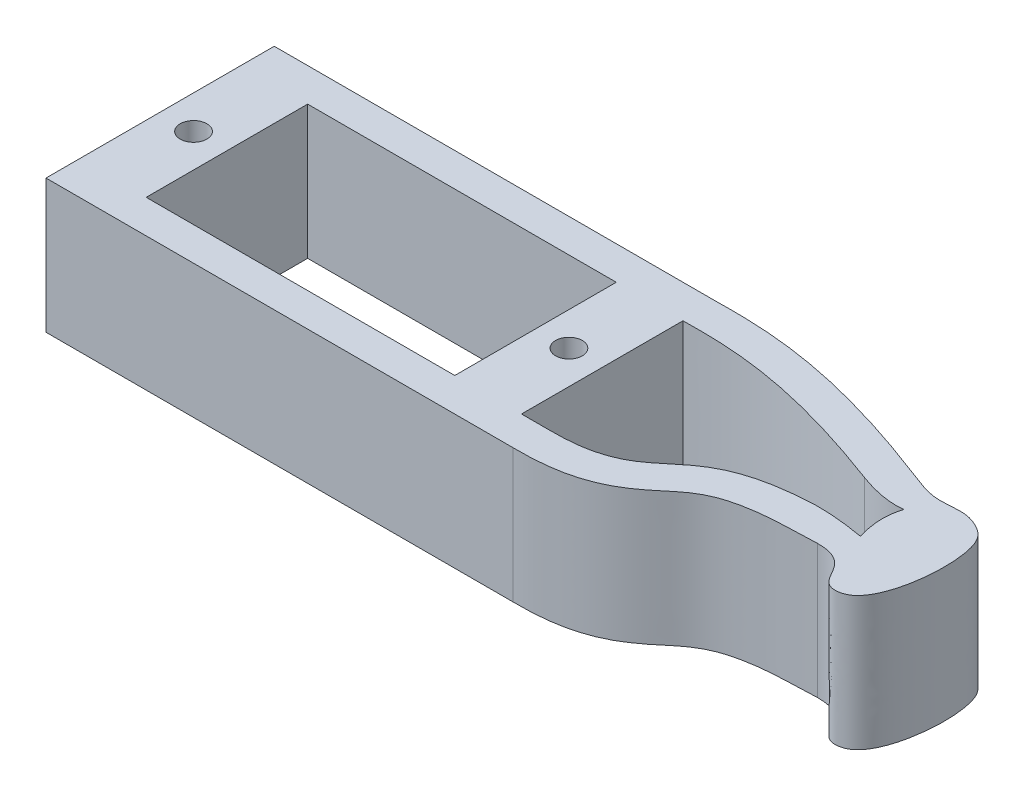
SolidWorks part; units mm, degrees
ref_plane "Спереди" through (0, 0, 0) normal (0, 0, 1) x (1, 0, 0)
ref_plane "Сверху" through (0, 0, 0) normal (0, 1, 0) x (1, 0, 0)
ref_plane "Справа" through (0, 0, 0) normal (1, 0, 0) x (0, 0, -1)
other "Configuration Table"
sketch "Эскиз1" plane through (0, 0, 0) normal (0, 1, 0) x (1, 0, 0)
  line L0 (0, 0) -> (0, -12.0852)
  line L1 (0, -12.0852) -> (23.1, -12.0852)
  line L2 (0, -12.0852) -> (28.092, -12.0852) construction
  line L3 (28.092, -12.0852) -> (28.092, 0) construction
  line L4 (0, 0) -> (23.1, 0)
  line L5 (23.1, -6.0426) -> (28.1, -6.0425) construction
  line L7 (-2.5, 2.5) -> (28.071, 2.5)
  line L9 (-2.5, -14.5852) -> (29.9653, -14.5852)
  line L11 (47.5572, -1.6341) -> (47.5572, -9.3909) construction
  line L13 (28.092, -12.0852) -> (29.9852, -12.0852)
  line L14 (0, -6.0426) -> (-5, -6.0426) construction
  line L15 (23.1, -12.0852) -> (23.1, 0)
  line L16 (0, -12.0852) -> (29.9852, -12.0852) construction
  line L17 (0, 0) -> (28.092, 0) construction
  line L18 (45.0572, -3.368) -> (45.0572, -6.9843) construction
  line L19 (-2.5, 2.5) -> (-5, 2.5)
  line L20 (-5, 2.5) -> (-5, -14.5852)
  line L21 (-5, -14.5852) -> (-2.5, -14.5852)
  line L22 (28.092, 0) -> (28.092, -12.0852)
  line L23 (-2.5, 2.5) -> (-2.5, -14.5852) construction
  circle A0 centre (-2.5, -6.0426) radius 1
  circle A1 centre (25.6, -6.0425) radius 1
  spline S0 degree 3 poles (29.9852, -12.0852) (38.2811, -12.2209) (35.1725, -7.3609) (45.0572, -6.9843) knots 0 0 0 0 1 1 1 1
  spline S1 degree 3 poles (28.092, 0) (31.819, 0.063) (36.1454, -0.0333) (45.0572, -3.368) knots 0.142072 0.142072 0.142072 0.142072 1 1 1 1
  spline S2 degree 1 poles (28.071, 2.5) (47.5572, -1.6341) knots 0 0 1 1 construction
  spline S3 degree 1 poles (29.9653, -14.5852) (47.5572, -9.3909) knots 0 0 1 1 construction
  spline S4 degree 3 poles (28.071, 2.5) (28.3289, 2.5043) (28.8356, 2.5112) (29.9219, 2.5121) (31.9642, 2.4575) (34.7071, 2.1687) (37.9974, 1.4859) (40.7939, 0.735) (43.9534, -0.2798) (46.3857, -1.1957) (47.5572, -1.6341) knots 0.143669 0.143669 0.143669 0.143669 0.200447 0.257224 0.370779 0.597889 0.711444 0.824999 0.938554 1.052109 1.052109 1.052109 1.052109
  spline S5 degree 3 poles (47.5572, -9.3909) (47.2235, -9.4036) (46.5554, -9.4289) (45.7237, -9.4612) (45.051, -9.4855) (44.4754, -9.5142) (43.5206, -9.5889) (42.3958, -9.7499) (40.9997, -10.0913) (39.888, -10.5955) (38.9006, -11.3108) (37.7108, -12.3642) (36.2078, -13.3956) (34.6306, -14.0302) (33.2811, -14.3705) (32.0031, -14.5317) (30.8848, -14.5872) (30.2669, -14.5898) (29.9653, -14.5852) knots 0.000757 0.000757 0.000757 0.000757 0.034518 0.068278 0.085159 0.102039 0.135799 0.203321 0.270842 0.405884 0.540926 0.675969 0.811011 0.878532 0.946053 1.013574 1.047335 1.081095 1.081095 1.081095 1.081095
  spline S6 degree 3 poles (47.5572, -1.6341) (49.84, -2.5785) (50.7906, -1.1758) (54.3502, -3.7152) (53.8106, -11.5109) (49.6149, -12.022) (50.2446, -9.3573) (47.5572, -9.3909) knots 0 0 0 0 0.410599 0.487696 0.739498 0.793876 1 1 1 1
  spline S7 degree 2 poles (45.0572, -6.9843) (46.5962, -6.9607) (48.7103, -7.3258) knots 0 0 0 1 1 1
  spline S8 degree 2 poles (45.0572, -3.368) (47.1811, -4.1418) (48.5973, -3.9631) knots 0 0 0 1 1 1
  spline S9 degree 3 poles (48.7103, -7.3258) (48.3453, -6.1976) (48.2431, -5.0095) (48.5973, -3.9631) knots 0 0 0 0 1 1 1 1
  dimension "D1" = 2.5
extrude "Бобышка-Вытянуть1" add sketch "Эскиз1" along normal blind 10
